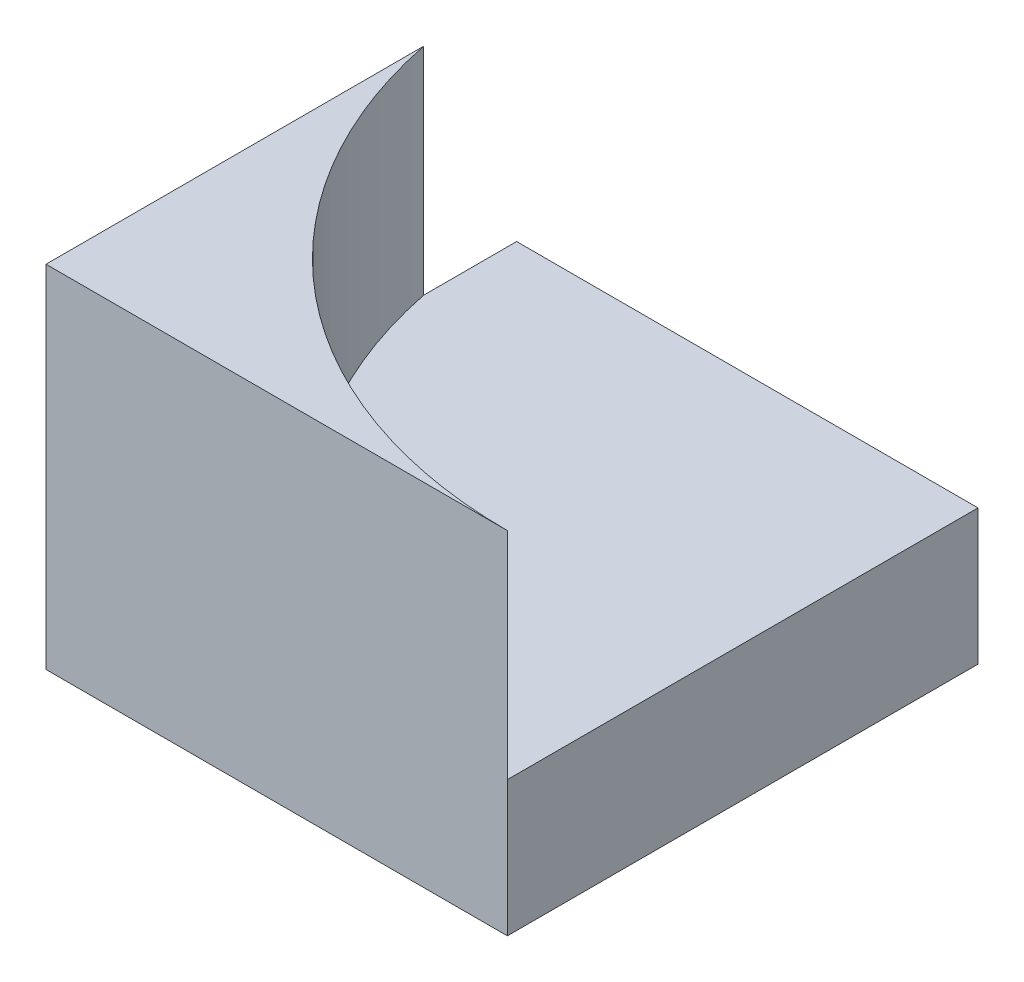
SolidWorks part; units mm, degrees
ref_plane "Front Plane" through (0, 0, 0) normal (1, 0, 0) x (0, 1, 0)
ref_plane "Top Plane" through (0, 0, 0) normal (0, 0, 1) x (0, 1, 0)
ref_plane "Right Plane" through (0, 0, 0) normal (0, 1, 0) x (-1, 0, 0)
sketch "Sketch1" plane through (0, 0, 0) normal (1, 0, 0) x (0, 1, 0)
  line L1 (0, 0) -> (-73.7961, 0)
  line L2 (0, 0) -> (0, -98.9469)
  line L3 (0, -98.9469) -> (-73.7961, -98.9469)
  line L4 (-73.7961, 0) -> (-73.7961, -98.9469)
extrude "Boss-Extrude1" add sketch "Sketch1" along normal blind 97
sketch "Sketch2" plane through (97, 0, 0) normal (1, 0, 0) x (0, 1, 0)
  line L0 (-73.7961, -98.9469) -> (0, -98.9469) construction
  line L1 (0, 0) -> (-45.3441, 0)
  line L2 (0, 0) -> (0, -98.9469)
  line L3 (0, -98.9469) -> (-45.3441, -98.9469)
  line L4 (-45.3441, 0) -> (-45.3441, -98.9469)
revolve "Cut-Revolve1" cut sketch "Sketch2" angle 360 about L3
